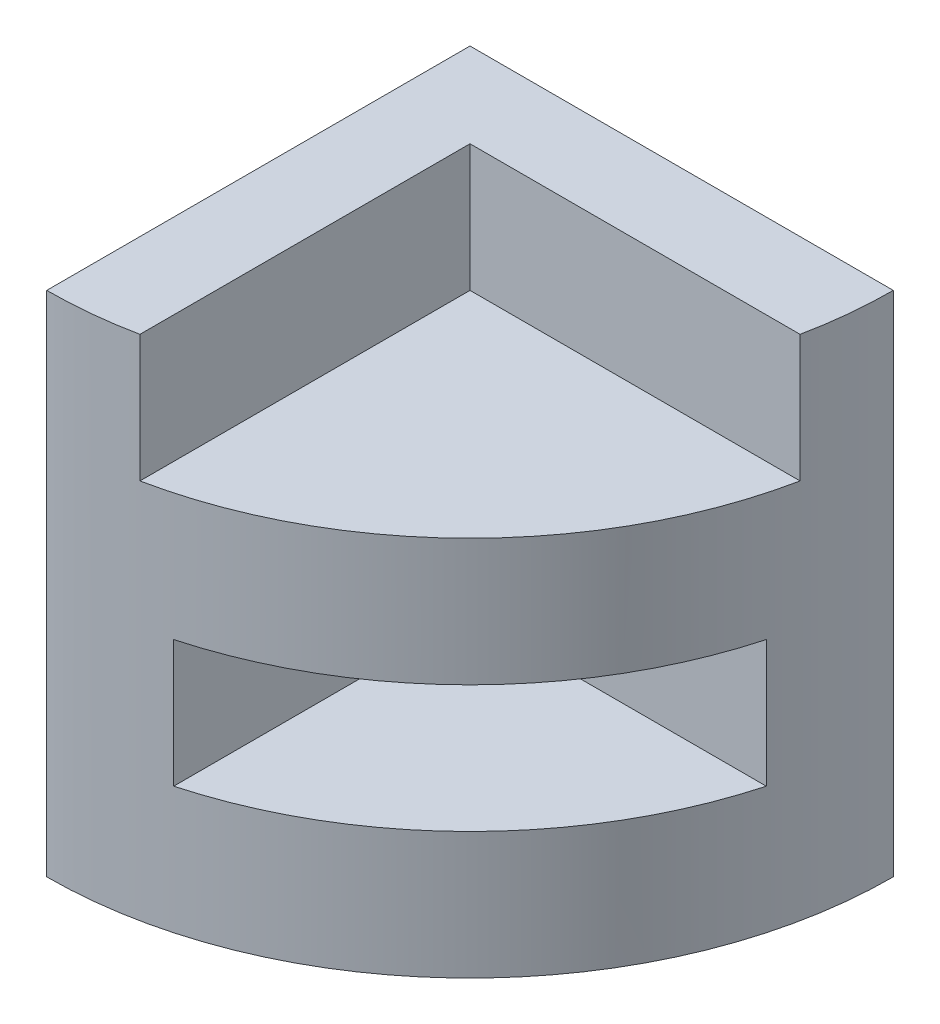
SolidWorks part; units mm, degrees
ref_plane "Front Plane" through (0, 0, 0) normal (0, 0, 1) x (1, 0, 0)
ref_plane "Top Plane" through (0, 0, 0) normal (0, 1, 0) x (1, 0, 0)
ref_plane "Right Plane" through (0, 0, 0) normal (1, 0, 0) x (0, 0, -1)
sketch "Sketch1" plane through (0, 0, 0) normal (0, 1, 0) x (1, 0, 0)
  line L0 (0, 0) -> (5, 0)
  line L1 (0, -5) -> (0, 0)
  arc A0 (5, 0) -> (0, -5) centre (0, 0) cw
  dimension "D1" = 5
extrude "Boss-Extrude1" add sketch "Sketch1" along normal blind 4.5
sketch "Sketch2" plane through (0, 4.5, 0) normal (0, 1, 0) x (1, 0, 0)
  line L0 (4.8221, -1.3221) -> (1.3221, -1.3221)
  line L1 (1.3221, -1.3221) -> (1.3221, -4.8221)
  arc A0 (0, -5) -> (5, 0) centre (0, 0) ccw construction
  arc A1 (1.3221, -4.8221) -> (4.8221, -1.3221) centre (0, 0) ccw
  dimension "D1" = 3.5
extrude "Cut-Extrude1" cut sketch "Sketch2" against normal blind 1.5 from offset 1.5 offset against normal yes
sketch "Sketch3" plane through (0, 4.5, 0) normal (0, 1, 0) x (1, 0, 0)
  line L0 (4.899, -1) -> (1, -1)
  line L1 (1, -1) -> (1, -4.899)
  line L2 (0, 0) -> (0, -5)
  line L3 (5, 0) -> (0, 0)
  line L4 (0, 0) -> (0, -5)
  line L5 (5, 0) -> (0, 0)
  arc A0 (4.899, -1) -> (5, 0) centre (0, 0) ccw
  arc A1 (0, -5) -> (5, 0) centre (0, 0) ccw
  arc A2 (0, -5) -> (1, -4.899) centre (0, 0) ccw
  dimension "D2" = 1
  dimension "D1" = 0
extrude "Boss-Extrude2" add sketch "Sketch3" along normal blind 1.5
